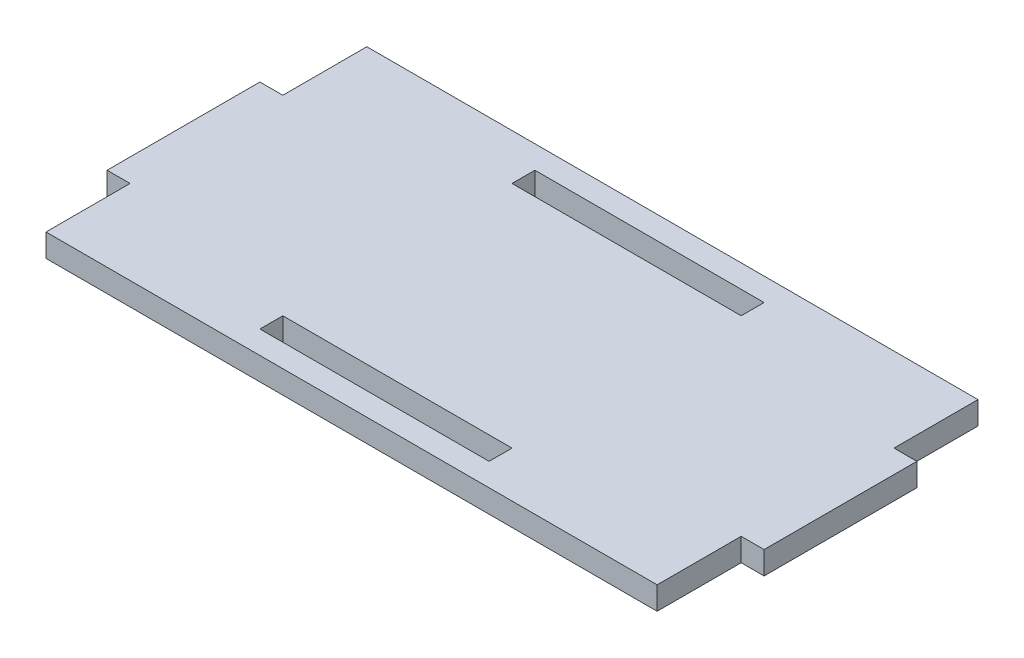
SolidWorks part; units mm, degrees
material "ABS"
ref_plane "Front Plane" through (0, 0, 0) normal (0, 0, 1) x (1, 0, 0)
ref_plane "Top Plane" through (0, 0, 0) normal (0, 1, 0) x (1, 0, 0)
ref_plane "Right Plane" through (0, 0, 0) normal (1, 0, 0) x (0, 0, -1)
sketch "Sketch1" plane through (0, 0, 0) normal (0, 1, 0) x (1, 0, 0)
  line L0 (0, 31) -> (0, 42)
  line L1 (0, 0) -> (80, 0)
  line L2 (0, 0) -> (0, 11)
  line L3 (0, 42) -> (80, 42)
  line L4 (80, 0) -> (80, 11)
  line L5 (25, 39) -> (55, 39)
  line L6 (25, 39) -> (25, 36)
  line L7 (25, 36) -> (55, 36)
  line L8 (55, 39) -> (55, 36)
  line L9 (25, 3) -> (55, 3)
  line L10 (25, 3) -> (25, 6)
  line L11 (25, 6) -> (55, 6)
  line L12 (55, 3) -> (55, 6)
  line L13 (80, 31) -> (83, 31)
  line L15 (80, 11) -> (83, 11)
  line L16 (83, 31) -> (83, 11)
  line L17 (0, 31) -> (-3, 31)
  line L19 (0, 11) -> (-3, 11)
  line L20 (-3, 31) -> (-3, 11)
  line L21 (80, 31) -> (80, 42)
  dimension "D1" = 80
  dimension "D2" = 42
  dimension "D3" = 3
  dimension "D4" = 3
  dimension "D5" = 3
  dimension "D6" = 3
  dimension "D7" = 30
  dimension "D8" = 30
  dimension "D9" = 25
  dimension "D10" = 25
  dimension "D11" = 3
  dimension "D12" = 3
  dimension "D13" = 20
  dimension "D14" = 20
  dimension "D15" = 11
  dimension "D16" = 11
extrude "Boss-Extrude1" add sketch "Sketch1" along normal blind 3
